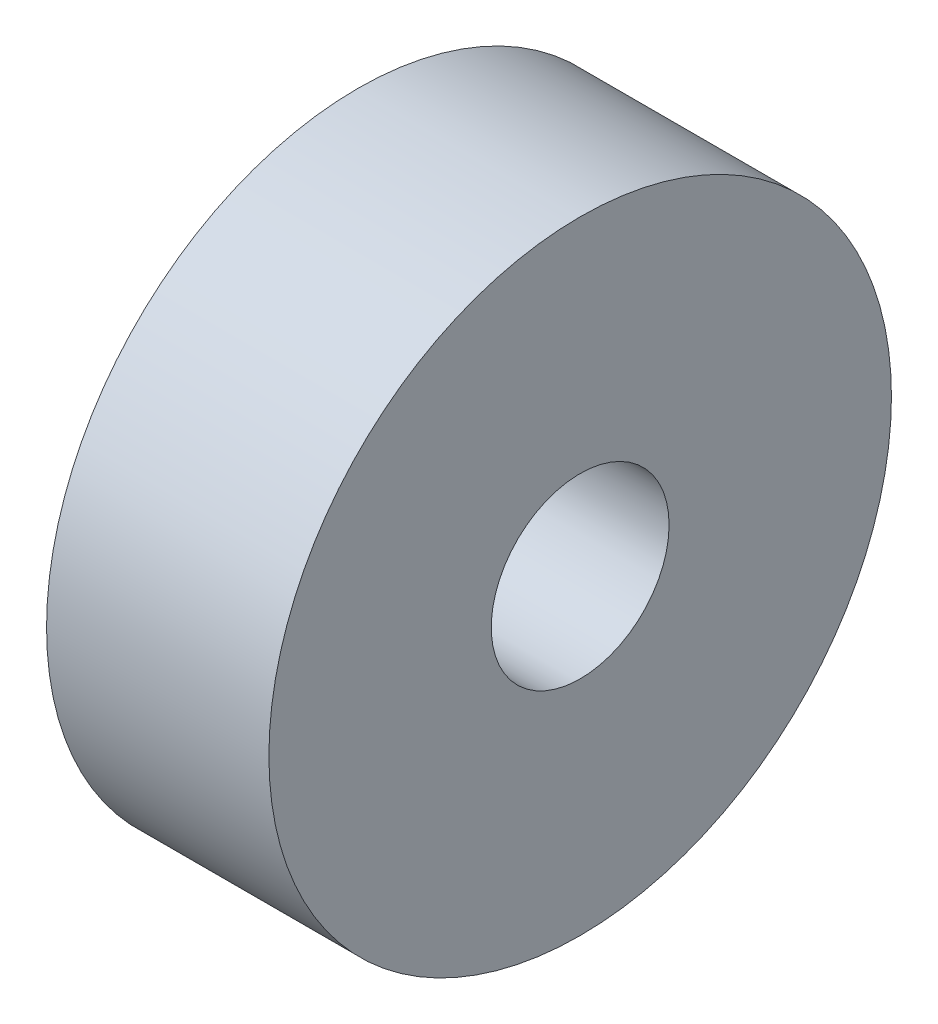
SolidWorks part; units mm, degrees
ref_plane "Front Plane" through (0, 0, 0) normal (0, 0, 1) x (1, 0, 0)
ref_plane "Top Plane" through (0, 0, 0) normal (0, 1, 0) x (1, 0, 0)
ref_plane "Right Plane" through (0, 0, 0) normal (1, 0, 0) x (0, 0, -1)
sketch "Sketch1" plane through (0, 0, 0) normal (1, 0, 0) x (0, 0, -1)
  circle A0 centre (0, 0) radius 100
  circle A1 centre (0, 0) radius 350
  dimension "D1" = 200
  dimension "D2" = 700
extrude "Boss-Extrude1" add sketch "Sketch1" along normal mid plane 250
